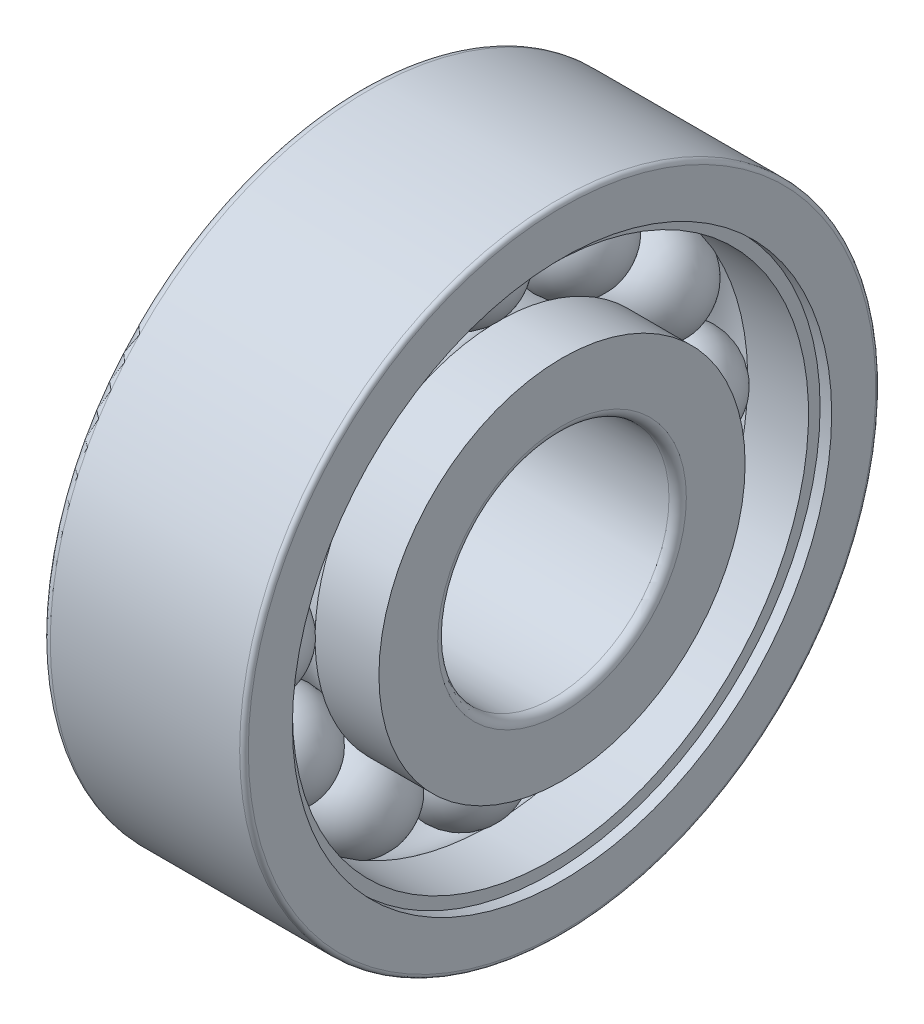
SolidWorks part; units mm, degrees
ref_plane "Front" through (0, 0, 0) normal (0, 0, 1) x (1, 0, 0)
ref_plane "Top" through (0, 0, 0) normal (0, 1, 0) x (1, 0, 0)
ref_plane "Right" through (0, 0, 0) normal (1, 0, 0) x (0, 0, -1)
sketch "Sketch1" plane through (0, 0, 0) normal (0, 0, 1) x (1, 0, 0)
  line L0 (-3.0919, 0) -> (2.899, 0) construction
  line L1 (-3.0919, 7.5) -> (2.899, 7.5) construction
  line L2 (-1.75, 7.5) -> (1.75, 7.5)
  arc A0 (-1.75, 7.5) -> (1.75, 7.5) centre (0, 7.5) ccw
  dimension "R" = 1.75
  dimension "D1" = 7.5
revolve "Revolve1" add sketch "Sketch1" angle 360 about L1
sketch "Sketch2" plane through (0, 0, 0) normal (0, 0, 1) x (1, 0, 0)
  line L0 (-3.5, 6.3333) -> (-1.2909, 6.3333)
  line L1 (3.5, 6.3333) -> (3.5, 4)
  line L2 (3.5, 4) -> (-3.5, 4)
  line L3 (-3.5, 4) -> (-3.5, 6.3333)
  line L4 (-2.9924, 0) -> (3.9982, 0) construction
  line L5 (-1.8743, 7.5) -> (3.1755, 7.5) construction
  line L7 (1.2909, 6.3333) -> (3.5, 6.3333)
  line L8 (-3.5, 6.2861) -> (-3.5, 1.454) construction
  arc A0 (-1.2909, 6.3333) -> (1.2909, 6.3333) centre (0, 7.5) ccw
  dimension "D1" = 7.5
  dimension "B" = 7
  dimension "D2" = 1.74
  dimension "d" = 8
  dimension "D3" = 12.6667
  dimension "T" = 7
  dimension "D6" = 3.5
revolve "Revolve2" add sketch "Sketch2" angle 360 about L4
sketch "Sketch3" plane through (0, 0, 0) normal (0, 0, 1) x (1, 0, 0)
  line L0 (-3.5, 8.6667) -> (-3.5, 11)
  line L1 (-3.5, 11) -> (3.5, 11)
  line L2 (3.5, 11) -> (3.5, 9.3267)
  line L3 (3.1, 8.9267) -> (0.9961, 8.9267)
  line L4 (-2.9924, 0) -> (3.4329, 0) construction
  line L6 (-1.7375, 7.5) -> (2.2712, 7.5) construction
  line L7 (-1.2909, 8.6667) -> (-3.5, 8.6667)
  line L8 (3.1, 8.9267) -> (3.1, 9.3267)
  line L9 (3.1, 9.3267) -> (3.5, 9.3267)
  arc A0 (0.9961, 8.9267) -> (-1.2909, 8.6667) centre (0, 7.5) ccw
  dimension "D1" = 7.5
  dimension "D4" = 1.74
  dimension "B" = 7
  dimension "DD" = 22
  dimension "D3" = 17.8533
  dimension "D5" = 17.3333
  dimension "D6" = 0.4
  dimension "D7" = 0.4
  dimension "D2" = 3.5
revolve "Revolve3" add sketch "Sketch3" angle 360 about L4
pattern_circular "Circular-Pattern1" count 12 over 360 about axis through (0, 0, 0) along (1, 0, 0) of "Revolve1"
fillet "Fillet1" radius 0.3 2 edges at (3.5, 0, 4) (-3.5, 0, 11)
fillet "Fillet2" radius 0.15 2 edges at (3.5, 0, 11) (-3.5, 0, 4)
equation "\"R@Sketch1\" =  ( \"DD@Sketch3\" - \"d@Sketch2\" )  / 8"
equation "\"D1@Sketch1\"=(\"d@Sketch2\"+\"DD@Sketch3\")/4"
equation "\"D1@Sketch2\"=(\"d@Sketch2\"+\"DD@Sketch3\")/4"
equation "\"D3@Sketch2\" =  \"d@Sketch2\"+  ( \"DD@Sketch3\" - \"d@Sketch2\" )  /3"
equation "\"D2@Sketch2\" =  ( \"DD@Sketch3\" - \"d@Sketch2\" )  / 8 - 0.01"
equation "\"D6@Sketch2\" = \"B@Sketch2\" / 2"
equation "\"B@Sketch3\" = \"B@Sketch2\""
equation "\"D2@Sketch3\" = \"B@Sketch3\" / 2"
equation "\"D1@Sketch3\"=(\"d@Sketch2\"+\"DD@Sketch3\")/4"
equation "\"D3@Sketch3\" = (  \"DD@Sketch3\" -  (\"DD@Sketch3\" - \"d@Sketch2\"  )  / 3 )  * 1.03"
equation "\"D5@Sketch3\" = \"DD@Sketch3\" -  (  \"DD@Sketch3\" - \"d@Sketch2\")  / 3"
equation "\"D6@Sketch3\" = \"d@Sketch2\" / 20"
equation "\"D7@Sketch3\"=\"D6@Sketch3\""
equation "\"D4@Sketch3\"=(\"DD@Sketch3\"-\"d@Sketch2\")/8-0.01"
equation "\"m@Circular-Pattern1\" = int( 3.14159265 / atn(\"R@Sketch1\" / sqr((\"d@Sketch2\"+\"DD@Sketch3\")/4 * (\"d@Sketch2\"+\"DD@Sketch3\")/4 - \"R@Sketch1\" *  \"R@Sketch1\")))-1"
